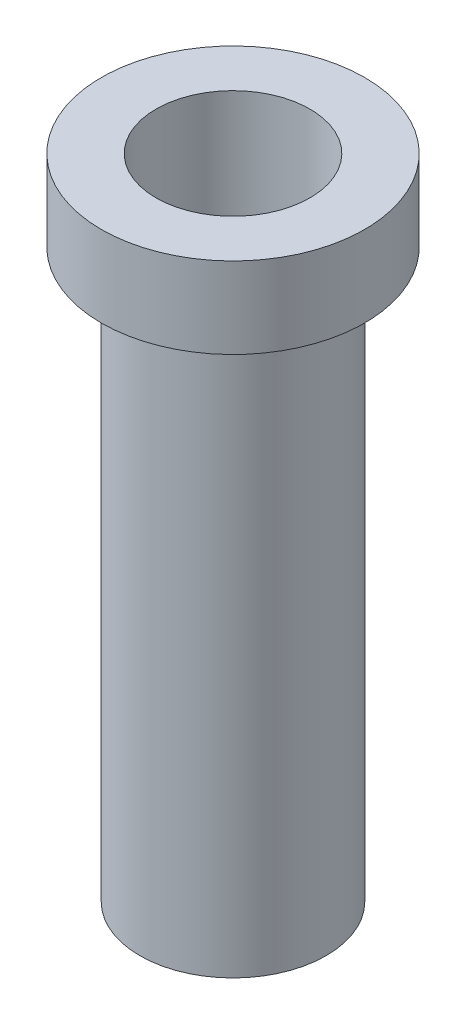
SolidWorks part; units mm, degrees
ref_plane "Front Plane" through (0, 0, 0) normal (0, 0, 1) x (1, 0, 0)
ref_plane "Top Plane" through (0, 0, 0) normal (0, 1, 0) x (1, 0, 0)
ref_plane "Right Plane" through (0, 0, 0) normal (1, 0, 0) x (0, 0, -1)
sketch "Sketch1" plane through (0, 0, 0) normal (0, 1, 0) x (1, 0, 0)
  circle A0 centre (0, 0) radius 3.25
extrude "Boss-Extrude1" add sketch "Sketch1" along normal blind 2
sketch "Sketch2" plane through (0, 0, 0) normal (0, -1, 0) x (-1, 0, 0)
  circle A0 centre (0, 0) radius 2.3
extrude "Boss-Extrude2" add sketch "Sketch2" along normal blind 14
sketch "Sketch4" plane through (0, 2, 0) normal (0, 1, 0) x (1, 0, 0)
  circle A0 centre (0, 0) radius 1.9
extrude "Cut-Extrude1" cut sketch "Sketch4" against normal through all
